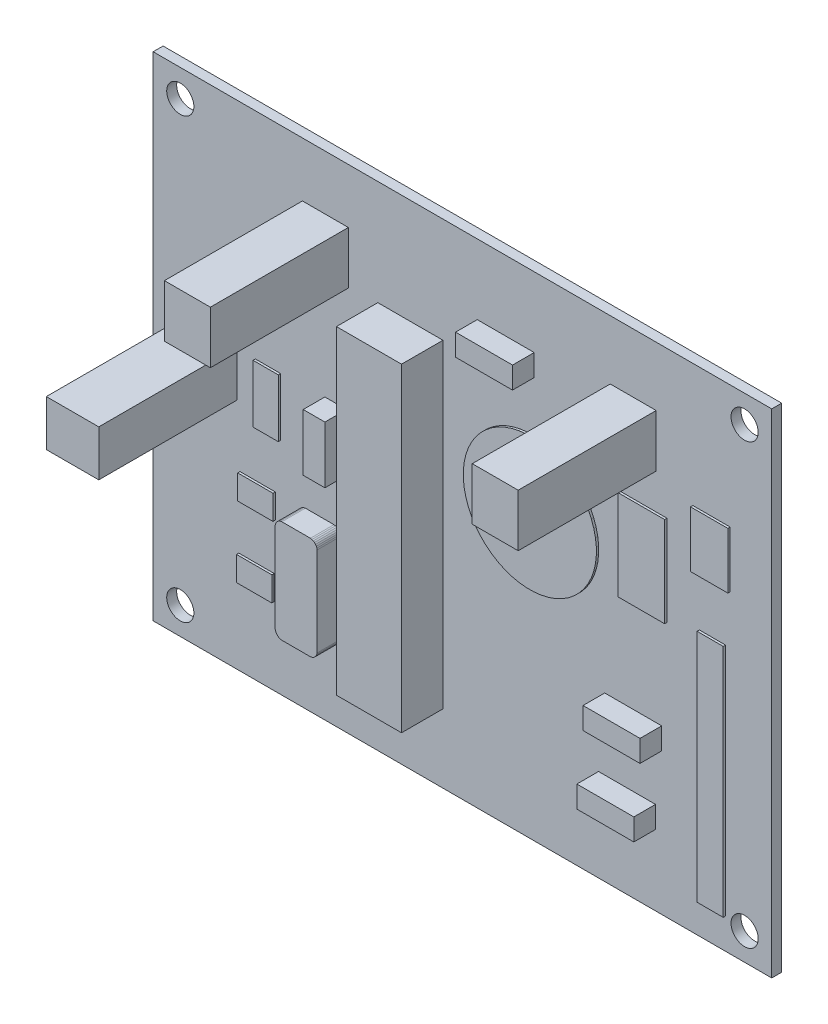
SolidWorks part; units mm, degrees
ref_plane "Front Plane" through (0, 0, 0) normal (0, 0, 1) x (1, 0, 0)
ref_plane "Top Plane" through (0, 0, 0) normal (0, 1, 0) x (1, 0, 0)
ref_plane "Right Plane" through (0, 0, 0) normal (1, 0, 0) x (0, 0, -1)
sketch "Sketch1" plane through (0, 0, 0) normal (0, 0, 1) x (1, 0, 0)
  line L0 (0, 0.1) -> (68.4, 0.1)
  line L1 (68.4, 0.1) -> (68.4, 54.6)
  line L2 (68.4, 54.6) -> (0, 54.6)
  line L3 (0, 54.6) -> (0, 0.1)
extrude "BOARD" add sketch "Sketch1" along normal blind 1.1 separate body
ref_plane "Plane1" through (0, 0, 1.1) normal (0, 0, 1) x (1, 0, 0)
sketch "Sketch2" plane through (0, 0, 1.1) normal (0, 0, 1) x (1, 0, 0)
  line L0 (63.29, 3.479) -> (60.4, 3.479)
  line L1 (60.4, 3.479) -> (60.4, 29.429)
  line L2 (60.4, 29.429) -> (63.29, 29.429)
  line L3 (63.29, 29.429) -> (63.29, 3.479)
extrude "FP-61301011121-MFG-1" add sketch "Sketch2" along normal blind 0.254 separate body
sketch "Sketch3" plane through (0, 0, 1.1) normal (0, 0, 1) x (1, 0, 0)
  line L0 (56.805, 28.355) -> (51.645, 28.355)
  line L1 (51.645, 28.355) -> (51.645, 38.335)
  line L2 (51.645, 38.335) -> (56.805, 38.335)
  line L3 (56.805, 38.335) -> (56.805, 28.355)
extrude "FP-3296W-MFG-1" add sketch "Sketch3" along normal blind 0.254 separate body
sketch "Sketch4" plane through (0, 0, 1.1) normal (0, 0, 1) x (1, 0, 0)
  line L0 (55.55, 7.9) -> (49.25, 7.9)
  line L1 (49.25, 7.9) -> (49.25, 10.3)
  line L2 (49.25, 10.3) -> (55.55, 10.3)
  line L3 (55.55, 10.3) -> (55.55, 7.9)
extrude "RESA60-630X240-1" add sketch "Sketch4" along normal blind 2.3984 separate body
sketch "Sketch5" plane through (0, 0, 1.1) normal (0, 0, 1) x (1, 0, 0)
  line L0 (56.232, 15.762) -> (49.932, 15.762)
  line L1 (49.932, 15.762) -> (49.932, 18.162)
  line L2 (49.932, 18.162) -> (56.232, 18.162)
  line L3 (56.232, 18.162) -> (56.232, 15.762)
extrude "RESA60-630X240-2" add sketch "Sketch5" along normal blind 2.3984 separate body
sketch "Sketch6" plane through (0, 0, 1.1) normal (0, 0, 1) x (1, 0, 0)
  line L0 (21.389, 31.034) -> (21.389, 24.734)
  line L1 (21.389, 24.734) -> (18.989, 24.734)
  line L2 (18.989, 24.734) -> (18.989, 31.034)
  line L3 (18.989, 31.034) -> (21.389, 31.034)
extrude "RESA60-630X240-3" add sketch "Sketch6" along normal blind 2.3984 separate body
sketch "Sketch7" plane through (0, 0, 1.1) normal (0, 0, 1) x (1, 0, 0)
  line L0 (42.135, 44.464) -> (35.835, 44.464)
  line L1 (35.835, 44.464) -> (35.835, 46.864)
  line L2 (35.835, 46.864) -> (42.135, 46.864)
  line L3 (42.135, 46.864) -> (42.135, 44.464)
extrude "RESA60-630X240-4" add sketch "Sketch7" along normal blind 2.3984 separate body
sketch "Sketch8" plane through (0, 0, 1.1) normal (0, 0, 1) x (1, 0, 0)
  line L0 (55.6222, 42.2562) -> (50.5422, 42.2562)
  line L1 (50.5422, 42.2562) -> (50.5422, 48.0561)
  line L2 (50.5422, 48.0561) -> (55.6222, 48.0561)
  line L3 (55.6222, 48.0561) -> (55.6222, 42.2562)
extrude "MOLX-22-27-2021_V-1" add sketch "Sketch8" along normal blind 15.26 separate body
sketch "Sketch9" plane through (0, 0, 1.1) normal (0, 0, 1) x (1, 0, 0)
  line L0 (16.5058, 48.5638) -> (21.5858, 48.5638)
  line L1 (21.5858, 48.5638) -> (21.5858, 42.7639)
  line L2 (21.5858, 42.7639) -> (16.5058, 42.7639)
  line L3 (16.5058, 42.7639) -> (16.5058, 48.5638)
extrude "MOLX-22-27-2021_V-2" add sketch "Sketch9" along normal blind 15.26 separate body
sketch "Sketch10" plane through (0, 0, 1.1) normal (0, 0, 1) x (1, 0, 0)
  line L0 (9.2458, 30.9322) -> (9.2458, 25.8522)
  line L1 (9.2458, 25.8522) -> (3.4459, 25.8522)
  line L2 (3.4459, 25.8522) -> (3.4459, 30.9322)
  line L3 (3.4459, 30.9322) -> (9.2458, 30.9322)
extrude "MOLX-22-27-2021_V-3" add sketch "Sketch10" along normal blind 15.26 separate body
sketch "LED-2P-2.54-3MM_V-1" plane through (0, 0, 1.1) normal (0, 0, 1) x (1, 0, 0)
  line L0 (41.2537, 12.1367) -> (41.661, 12.022)
  line L1 (41.661, 12.022) -> (42.0364, 11.8268)
  line L2 (42.0364, 11.8268) -> (42.2649, 11.6403)
  line L3 (42.2649, 11.6403) -> (42.4407, 11.6403)
  line L4 (42.4407, 11.6403) -> (42.4407, 11.465)
  line L5 (42.4407, 11.465) -> (42.4975, 11.3949)
  line L6 (42.4975, 11.3949) -> (42.4976, 11.3947)
  line L7 (42.4976, 11.3947) -> (42.4976, 11.3948)
  line L8 (42.4976, 11.3948) -> (42.4976, 8.8051)
  line L9 (42.4976, 8.8051) -> (42.4407, 8.7348)
  line L10 (42.4407, 8.7348) -> (42.4407, 8.5598)
  line L11 (42.4407, 8.5598) -> (42.2653, 8.5598)
  line L12 (42.2653, 8.5598) -> (42.0366, 8.3731)
  line L13 (42.0366, 8.3731) -> (41.6612, 8.1779)
  line L14 (41.6612, 8.1779) -> (41.2539, 8.0631)
  line L15 (41.2539, 8.0631) -> (40.8318, 8.0337)
  line L16 (40.8318, 8.0337) -> (40.4125, 8.0908)
  line L17 (40.4125, 8.0908) -> (40.0137, 8.2321)
  line L18 (40.0137, 8.2321) -> (39.652, 8.4517)
  line L19 (39.652, 8.4517) -> (39.536, 8.5598)
  line L20 (39.536, 8.5598) -> (39.361, 8.5598)
  line L21 (39.361, 8.5598) -> (39.361, 8.7231)
  line L22 (39.361, 8.7231) -> (39.3425, 8.7403)
  line L23 (39.3425, 8.7403) -> (39.0983, 9.0859)
  line L24 (39.0983, 9.0859) -> (38.9296, 9.4739)
  line L25 (38.9296, 9.4739) -> (38.8434, 9.8882)
  line L26 (38.8434, 9.8882) -> (38.8434, 10.3114)
  line L27 (38.8434, 10.3114) -> (38.9295, 10.7257)
  line L28 (38.9295, 10.7257) -> (39.0982, 11.1137)
  line L29 (39.0982, 11.1137) -> (39.3424, 11.4593)
  line L30 (39.3424, 11.4593) -> (39.361, 11.4767)
  line L31 (39.361, 11.4767) -> (39.361, 11.6403)
  line L32 (39.361, 11.6403) -> (39.5364, 11.6403)
  line L33 (39.5364, 11.6403) -> (39.6518, 11.748)
  line L34 (39.6518, 11.748) -> (40.0135, 11.9676)
  line L35 (40.0135, 11.9676) -> (40.4123, 12.1089)
  line L36 (40.4123, 12.1089) -> (40.8316, 12.1661)
  line L37 (40.8316, 12.1661) -> (41.2537, 12.1367)
sketch "LED-2P-2.54-3MM_V-2" plane through (0, 0, 1.1) normal (0, 0, 1) x (1, 0, 0)
  line L0 (41.4537, 20.0367) -> (41.861, 19.922)
  line L1 (41.861, 19.922) -> (42.2364, 19.7268)
  line L2 (42.2364, 19.7268) -> (42.4649, 19.5403)
  line L3 (42.4649, 19.5403) -> (42.6407, 19.5403)
  line L4 (42.6407, 19.5403) -> (42.6407, 19.365)
  line L5 (42.6407, 19.365) -> (42.6975, 19.2949)
  line L6 (42.6975, 19.2949) -> (42.6976, 19.2947)
  line L7 (42.6976, 19.2947) -> (42.6976, 19.2948)
  line L8 (42.6976, 19.2948) -> (42.6976, 16.7051)
  line L9 (42.6976, 16.7051) -> (42.6407, 16.6348)
  line L10 (42.6407, 16.6348) -> (42.6407, 16.4598)
  line L11 (42.6407, 16.4598) -> (42.4653, 16.4598)
  line L12 (42.4653, 16.4598) -> (42.2366, 16.2731)
  line L13 (42.2366, 16.2731) -> (41.8612, 16.0779)
  line L14 (41.8612, 16.0779) -> (41.4539, 15.9631)
  line L15 (41.4539, 15.9631) -> (41.0318, 15.9337)
  line L16 (41.0318, 15.9337) -> (40.6125, 15.9908)
  line L17 (40.6125, 15.9908) -> (40.2137, 16.1321)
  line L18 (40.2137, 16.1321) -> (39.852, 16.3517)
  line L19 (39.852, 16.3517) -> (39.736, 16.4598)
  line L20 (39.736, 16.4598) -> (39.561, 16.4598)
  line L21 (39.561, 16.4598) -> (39.561, 16.6231)
  line L22 (39.561, 16.6231) -> (39.5425, 16.6403)
  line L23 (39.5425, 16.6403) -> (39.2983, 16.9859)
  line L24 (39.2983, 16.9859) -> (39.1296, 17.3739)
  line L25 (39.1296, 17.3739) -> (39.0434, 17.7882)
  line L26 (39.0434, 17.7882) -> (39.0434, 18.2114)
  line L27 (39.0434, 18.2114) -> (39.1295, 18.6257)
  line L28 (39.1295, 18.6257) -> (39.2982, 19.0137)
  line L29 (39.2982, 19.0137) -> (39.5424, 19.3593)
  line L30 (39.5424, 19.3593) -> (39.561, 19.3767)
  line L31 (39.561, 19.3767) -> (39.561, 19.5403)
  line L32 (39.561, 19.5403) -> (39.7364, 19.5403)
  line L33 (39.7364, 19.5403) -> (39.8518, 19.648)
  line L34 (39.8518, 19.648) -> (40.2135, 19.8676)
  line L35 (40.2135, 19.8676) -> (40.6123, 20.0089)
  line L36 (40.6123, 20.0089) -> (41.0316, 20.0661)
  line L37 (41.0316, 20.0661) -> (41.4537, 20.0367)
  point P38 (0, 0)
  point P39 (0, 0)
sketch "LED-2P-2.54-3MM_V-3" plane through (0, 0, 1.1) normal (0, 0, 1) x (1, 0, 0)
  line L0 (14.2537, 38.9367) -> (14.661, 38.822)
  line L1 (14.661, 38.822) -> (15.0364, 38.6268)
  line L2 (15.0364, 38.6268) -> (15.2649, 38.4403)
  line L3 (15.2649, 38.4403) -> (15.4407, 38.4403)
  line L4 (15.4407, 38.4403) -> (15.4407, 38.265)
  line L5 (15.4407, 38.265) -> (15.4975, 38.1949)
  line L6 (15.4975, 38.1949) -> (15.4976, 38.1947)
  line L7 (15.4976, 38.1947) -> (15.4976, 38.1948)
  line L8 (15.4976, 38.1948) -> (15.4976, 35.6051)
  line L9 (15.4976, 35.6051) -> (15.4407, 35.5348)
  line L10 (15.4407, 35.5348) -> (15.4407, 35.3598)
  line L11 (15.4407, 35.3598) -> (15.2653, 35.3598)
  line L12 (15.2653, 35.3598) -> (15.0366, 35.1731)
  line L13 (15.0366, 35.1731) -> (14.6612, 34.9779)
  line L14 (14.6612, 34.9779) -> (14.2539, 34.8631)
  line L15 (14.2539, 34.8631) -> (13.8318, 34.8337)
  line L16 (13.8318, 34.8337) -> (13.4125, 34.8908)
  line L17 (13.4125, 34.8908) -> (13.0137, 35.0321)
  line L18 (13.0137, 35.0321) -> (12.652, 35.2517)
  line L19 (12.652, 35.2517) -> (12.536, 35.3598)
  line L20 (12.536, 35.3598) -> (12.361, 35.3598)
  line L21 (12.361, 35.3598) -> (12.361, 35.5231)
  line L22 (12.361, 35.5231) -> (12.3425, 35.5403)
  line L23 (12.3425, 35.5403) -> (12.0983, 35.8859)
  line L24 (12.0983, 35.8859) -> (11.9296, 36.2739)
  line L25 (11.9296, 36.2739) -> (11.8434, 36.6882)
  line L26 (11.8434, 36.6882) -> (11.8434, 37.1114)
  line L27 (11.8434, 37.1114) -> (11.9295, 37.5257)
  line L28 (11.9295, 37.5257) -> (12.0982, 37.9137)
  line L29 (12.0982, 37.9137) -> (12.3424, 38.2593)
  line L30 (12.3424, 38.2593) -> (12.361, 38.2767)
  line L31 (12.361, 38.2767) -> (12.361, 38.4403)
  line L32 (12.361, 38.4403) -> (12.5364, 38.4403)
  line L33 (12.5364, 38.4403) -> (12.6518, 38.548)
  line L34 (12.6518, 38.548) -> (13.0135, 38.7676)
  line L35 (13.0135, 38.7676) -> (13.4123, 38.9089)
  line L36 (13.4123, 38.9089) -> (13.8316, 38.9661)
  line L37 (13.8316, 38.9661) -> (14.2537, 38.9367)
sketch "Sketch14" plane through (0, 0, 1.1) normal (0, 0, 1) x (1, 0, 0)
  line L0 (63.808, 34.785) -> (59.668, 34.785)
  line L1 (59.668, 34.785) -> (59.668, 40.985)
  line L2 (59.668, 40.985) -> (63.808, 40.985)
  line L3 (63.808, 40.985) -> (63.808, 34.785)
extrude "FP-TMM-103-03-T-S-MFG-1" add sketch "Sketch14" along normal blind 0.254 separate body
sketch "Sketch15" plane through (0, 0, 1.1) normal (0, 0, 1) x (1, 0, 0)
  line L0 (20.1515, 19.2764) -> (20.3017, 19.2142)
  line L1 (20.3017, 19.2142) -> (20.4368, 19.1239)
  line L2 (20.4368, 19.1239) -> (20.5517, 19.009)
  line L3 (20.5517, 19.009) -> (20.642, 18.8739)
  line L4 (20.642, 18.8739) -> (20.7042, 18.7237)
  line L5 (20.7042, 18.7237) -> (20.7359, 18.5643)
  line L6 (20.7359, 18.5643) -> (20.7359, 18.4831)
  line L7 (20.7359, 18.4831) -> (20.7359, 8.7831)
  line L8 (20.7359, 8.7831) -> (20.7359, 8.7018)
  line L9 (20.7359, 8.7018) -> (20.7042, 8.5425)
  line L10 (20.7042, 8.5425) -> (20.642, 8.3923)
  line L11 (20.642, 8.3923) -> (20.5517, 8.2572)
  line L12 (20.5517, 8.2572) -> (20.4368, 8.1423)
  line L13 (20.4368, 8.1423) -> (20.3017, 8.052)
  line L14 (20.3017, 8.052) -> (20.1516, 7.9898)
  line L15 (20.1516, 7.9898) -> (19.9922, 7.9581)
  line L16 (19.9922, 7.9581) -> (19.9109, 7.9581)
  line L17 (19.9109, 7.9581) -> (16.9109, 7.9581)
  line L18 (16.9109, 7.9581) -> (16.8296, 7.9581)
  line L19 (16.8296, 7.9581) -> (16.6703, 7.9898)
  line L20 (16.6703, 7.9898) -> (16.5201, 8.052)
  line L21 (16.5201, 8.052) -> (16.385, 8.1423)
  line L22 (16.385, 8.1423) -> (16.2701, 8.2572)
  line L23 (16.2701, 8.2572) -> (16.1798, 8.3923)
  line L24 (16.1798, 8.3923) -> (16.1176, 8.5424)
  line L25 (16.1176, 8.5424) -> (16.0859, 8.7018)
  line L26 (16.0859, 8.7018) -> (16.0859, 8.783)
  line L27 (16.0859, 8.783) -> (16.0859, 8.7831)
  line L28 (16.0859, 8.7831) -> (16.0859, 18.4831)
  line L29 (16.0859, 18.4831) -> (16.0859, 18.5643)
  line L30 (16.0859, 18.5643) -> (16.1176, 18.7237)
  line L31 (16.1176, 18.7237) -> (16.1798, 18.8739)
  line L32 (16.1798, 18.8739) -> (16.2701, 19.009)
  line L33 (16.2701, 19.009) -> (16.385, 19.1239)
  line L34 (16.385, 19.1239) -> (16.5201, 19.2142)
  line L35 (16.5201, 19.2142) -> (16.6703, 19.2764)
  line L36 (16.6703, 19.2764) -> (16.8296, 19.3081)
  line L37 (16.8296, 19.3081) -> (16.9109, 19.3081)
  line L38 (16.9109, 19.3081) -> (19.9109, 19.3081)
  line L39 (19.9109, 19.3081) -> (19.9921, 19.3081)
  line L40 (19.9921, 19.3081) -> (20.1515, 19.2764)
extrude "FOX-FOXSLF160-20-1" add sketch "Sketch15" along normal blind 2.6 separate body
sketch "Sketch16" plane through (0, 0, 1.1) normal (0, 0, 1) x (1, 0, 0)
  line L0 (32.044, 7.694) -> (24.844, 7.694)
  line L1 (24.844, 7.694) -> (24.844, 42.994)
  line L2 (24.844, 42.994) -> (32.044, 42.994)
  line L3 (32.044, 42.994) -> (32.044, 7.694)
extrude "28P3-1" add sketch "Sketch16" along normal blind 4.58 separate body
sketch "Sketch17" plane through (0, 0, 1.1) normal (0, 0, 1) x (1, 0, 0)
  line L0 (14.096, 24.43) -> (11.296, 24.43)
  line L1 (11.296, 24.43) -> (11.296, 30.83)
  line L2 (11.296, 30.83) -> (14.096, 30.83)
  line L3 (14.096, 30.83) -> (14.096, 24.43)
extrude "FP-K15H5-MFG-1" add sketch "Sketch17" along normal blind 0.254 separate body
sketch "Sketch18" plane through (0, 0, 1.1) normal (0, 0, 1) x (1, 0, 0)
  line L0 (13.376, 8.627) -> (9.476, 8.627)
  line L1 (9.476, 8.627) -> (9.476, 11.327)
  line L2 (9.476, 11.327) -> (13.376, 11.327)
  line L3 (13.376, 11.327) -> (13.376, 8.627)
extrude "FP-RCE0DB-MFG-1" add sketch "Sketch18" along normal blind 0.254 separate body
sketch "Sketch19" plane through (0, 0, 1.1) normal (0, 0, 1) x (1, 0, 0)
  line L0 (13.503, 16.501) -> (9.603, 16.501)
  line L1 (9.603, 16.501) -> (9.603, 19.201)
  line L2 (9.603, 19.201) -> (13.503, 19.201)
  line L3 (13.503, 19.201) -> (13.503, 16.501)
extrude "FP-RCE0DB-MFG-2" add sketch "Sketch19" along normal blind 0.254 separate body
sketch "Sketch20" plane through (0, 0, 1.1) normal (0, 0, 1) x (1, 0, 0)
  line L0 (43.1391, 38.7846) -> (43.9439, 38.6009)
  line L1 (43.9439, 38.6009) -> (44.7232, 38.3282)
  line L2 (44.7232, 38.3282) -> (45.4669, 37.97)
  line L3 (45.4669, 37.97) -> (46.1659, 37.5308)
  line L4 (46.1659, 37.5308) -> (46.8113, 37.0161)
  line L5 (46.8113, 37.0161) -> (47.3951, 36.4324)
  line L6 (47.3951, 36.4324) -> (47.9098, 35.7869)
  line L7 (47.9098, 35.7869) -> (48.349, 35.0879)
  line L8 (48.349, 35.0879) -> (48.7072, 34.3442)
  line L9 (48.7072, 34.3442) -> (48.9799, 33.5649)
  line L10 (48.9799, 33.5649) -> (49.1636, 32.7601)
  line L11 (49.1636, 32.7601) -> (49.256, 31.9398)
  line L12 (49.256, 31.9398) -> (49.256, 31.1142)
  line L13 (49.256, 31.1142) -> (49.1636, 30.2939)
  line L14 (49.1636, 30.2939) -> (48.9799, 29.4891)
  line L15 (48.9799, 29.4891) -> (48.7072, 28.7099)
  line L16 (48.7072, 28.7099) -> (48.349, 27.9661)
  line L17 (48.349, 27.9661) -> (47.9098, 27.2671)
  line L18 (47.9098, 27.2671) -> (47.3951, 26.6217)
  line L19 (47.3951, 26.6217) -> (46.8113, 26.0379)
  line L20 (46.8113, 26.0379) -> (46.1659, 25.5232)
  line L21 (46.1659, 25.5232) -> (45.4669, 25.084)
  line L22 (45.4669, 25.084) -> (44.7232, 24.7258)
  line L23 (44.7232, 24.7258) -> (43.9439, 24.4531)
  line L24 (43.9439, 24.4531) -> (43.1391, 24.2694)
  line L25 (43.1391, 24.2694) -> (42.3188, 24.177)
  line L26 (42.3188, 24.177) -> (41.4932, 24.177)
  line L27 (41.4932, 24.177) -> (40.6729, 24.2694)
  line L28 (40.6729, 24.2694) -> (39.8681, 24.4531)
  line L29 (39.8681, 24.4531) -> (39.0888, 24.7258)
  line L30 (39.0888, 24.7258) -> (38.3451, 25.084)
  line L31 (38.3451, 25.084) -> (37.6461, 25.5232)
  line L32 (37.6461, 25.5232) -> (37.0006, 26.0379)
  line L33 (37.0006, 26.0379) -> (36.4169, 26.6217)
  line L34 (36.4169, 26.6217) -> (35.9022, 27.2671)
  line L35 (35.9022, 27.2671) -> (35.463, 27.9661)
  line L36 (35.463, 27.9661) -> (35.1048, 28.7099)
  line L37 (35.1048, 28.7099) -> (34.8321, 29.4891)
  line L38 (34.8321, 29.4891) -> (34.6484, 30.2939)
  line L39 (34.6484, 30.2939) -> (34.556, 31.1143)
  line L40 (34.556, 31.1143) -> (34.556, 31.9398)
  line L41 (34.556, 31.9398) -> (34.6484, 32.7601)
  line L42 (34.6484, 32.7601) -> (34.8321, 33.5649)
  line L43 (34.8321, 33.5649) -> (35.1048, 34.3442)
  line L44 (35.1048, 34.3442) -> (35.463, 35.0879)
  line L45 (35.463, 35.0879) -> (35.9022, 35.7869)
  line L46 (35.9022, 35.7869) -> (36.4169, 36.4324)
  line L47 (36.4169, 36.4324) -> (37.0006, 37.0161)
  line L48 (37.0006, 37.0161) -> (37.6461, 37.5308)
  line L49 (37.6461, 37.5308) -> (38.3451, 37.97)
  line L50 (38.3451, 37.97) -> (39.0888, 38.3282)
  line L51 (39.0888, 38.3282) -> (39.8681, 38.6009)
  line L52 (39.8681, 38.6009) -> (40.6729, 38.7846)
  line L53 (40.6729, 38.7846) -> (41.4932, 38.877)
  line L54 (41.4932, 38.877) -> (42.3188, 38.877)
  line L55 (42.3188, 38.877) -> (43.1391, 38.7846)
extrude "FP-PS1440P02BT-MFG-1" add sketch "Sketch20" along normal blind 0.254 separate body
sketch "Sketch21" plane through (0, 0, 1.1) normal (0, 0, 1) x (1, 0, 0)
  line L0 (68.4, 54.6) -> (0, 54.6) construction
  line L1 (68.4, 0.1) -> (68.4, 54.6) construction
  line L2 (0, 54.6) -> (0, 0.1) construction
  line L3 (0, 0.1) -> (68.4, 0.1) construction
  circle A0 centre (65.4, 51.6) radius 1.5
  circle A1 centre (3, 51.6) radius 1.5
  circle A2 centre (3, 3.1) radius 1.5
  circle A3 centre (65.4, 3.1) radius 1.5
  dimension "D1" = 3
  dimension "D2" = 3
  dimension "D3" = 3
  dimension "D4" = 3
  dimension "D5" = 3
  dimension "D6" = 3
  dimension "D7" = 3
  dimension "D8" = 3
  dimension "D9" = 3
  dimension "D10" = 3
  dimension "D11" = 3
  dimension "D12" = 3
extrude "Cut-Extrude1" cut sketch "Sketch21" against normal up to next (1.1 mm away)
equation "\"D3@Sketch21\"=\"D1@Sketch21\""
equation "\"D4@Sketch21\"=\"D1@Sketch21\""
equation "\"D2@Sketch21\"=\"D1@Sketch21\""
